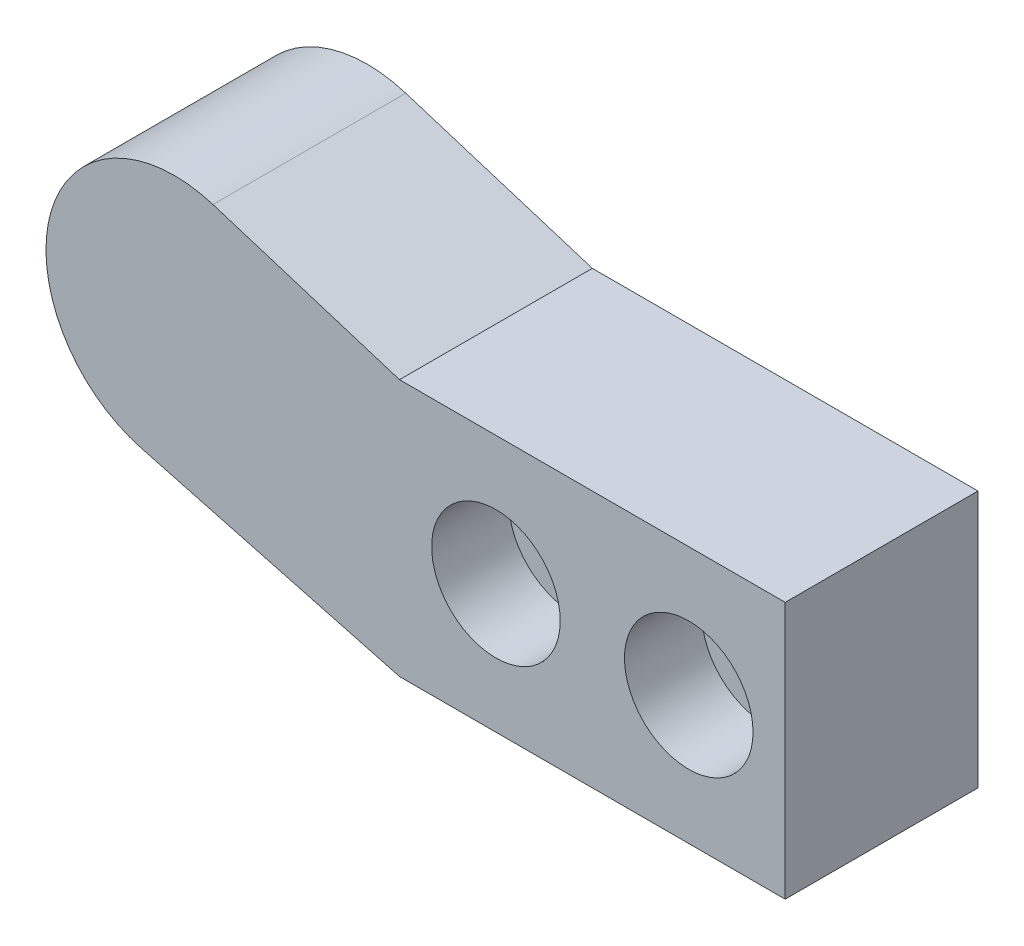
SolidWorks part; units mm, degrees
ref_plane "前视基准面" through (0, 0, 0) normal (0, 0, 1) x (1, 0, 0)
ref_plane "上视基准面" through (0, 0, 0) normal (0, 1, 0) x (1, 0, 0)
ref_plane "右视基准面" through (0, 0, 0) normal (1, 0, 0) x (0, 0, -1)
other "Configuration Table"
sketch "草图1" plane through (0, 0, 0) normal (0, 0, 1) x (1, 0, 0)
  line L0 (0, 0) -> (30, 0)
  line L1 (30, 0) -> (30, -20)
  line L2 (30, -20) -> (0, -20)
  line L3 (0, -10) -> (25424.3689, -10) construction
  line L5 (-17.5, -3.1284) -> (-17.5, -50003.1284) construction
  line L6 (0, -20) -> (-20.0694, -14.6643)
  line L7 (0, 0) -> (-14.5124, 4.5433)
  line L8 (0, 0) -> (0, -20) construction
  circle A1 centre (7.5, -10) radius 3
  circle A2 centre (22.5, -10) radius 3
  arc A3 (-14.5124, 4.5433) -> (-20.0694, -14.6643) centre (-17.5, -5) ccw
  dimension "D1" = 6
  dimension "D2" = 6
  dimension "D7" = 20
  dimension "D3" = 15
  dimension "D4" = 7.5
  dimension "D5" = 25
  dimension "D6" = 20
  dimension "D8" = 5
  dimension "D9" = 10
  dimension "D10" = 7.5
extrude "凸台-拉伸1" add sketch "草图1" along normal blind 15
sketch "草图2" plane through (0, 0, 15) normal (0, 0, 1) x (1, 0, 0)
  circle A0 centre (7.5, -10) radius 5
  circle A1 centre (22.5, -10) radius 5
  dimension "D1" = 10
  dimension "D2" = 10
extrude "切除-拉伸1" cut sketch "草图2" against normal blind 6
sketch "草图3" plane through (0, 0, 0) normal (0, 0, -1) x (-1, 0, 0)
  circle A0 centre (17.5, -5) radius 5
  dimension "D1" = 10
extrude "切除-拉伸2" cut sketch "草图3" against normal blind 3
sketch "草图4" plane through (0, 0, 3) normal (0, 0, -1) x (-1, 0, 0)
  circle A0 centre (17.5, -5) radius 2.5
  dimension "D1" = 5
extrude "切除-拉伸3" cut sketch "草图4" against normal blind 10
